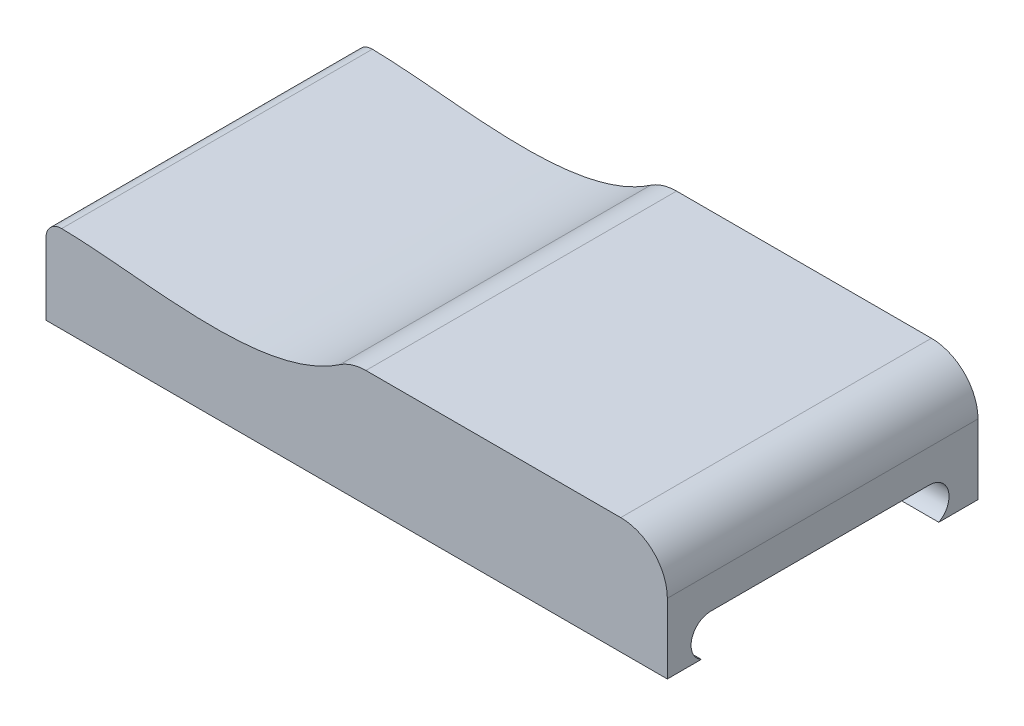
SolidWorks part; units mm, degrees
ref_plane "Front Plane" through (0, 0, 0) normal (0, 0, 1) x (1, 0, 0)
ref_plane "Top Plane" through (0, 0, 0) normal (0, 1, 0) x (1, 0, 0)
ref_plane "Right Plane" through (0, 0, 0) normal (1, 0, 0) x (0, 0, -1)
sketch "Sketch1" plane through (0, 0, 0) normal (0, 1, 0) x (1, 0, 0)
  line L1 (-200, -100) -> (200, -100)
  line L2 (-200, -100) -> (-200, 100)
  line L3 (-200, 100) -> (200, 100)
  line L4 (200, -100) -> (200, 100)
  line L5 (-200, -100) -> (200, 100) construction
  line L6 (-200, 100) -> (200, -100) construction
  point P0 (0, 0)
  dimension "D1" = 400
  dimension "D2" = 200
extrude "Boss-Extrude1" add sketch "Sketch1" along normal blind 60 contours L3 L4 L1 L2
sketch "Sketch3" plane through (0, 0, 100) normal (0, 0, 1) x (1, 0, 0)
  line L2 (-200, 60) -> (-200, 0) construction
  line L3 (-200, 60) -> (200, 60) construction
  line L4 (-200, 41.0333) -> (-200, 60)
  line L5 (-200, 60) -> (-3.947, 60)
  spline S0 degree 3 poles (-200, 41.0333) (-145.1623, 43.5654) (-56.827, 16.6615) (-3.947, 60) knots 0 0 0 0 1 1 1 1
extrude "Cut-Extrude1" cut sketch "Sketch3" against normal blind 220
fillet "Fillet1" radius 30 2 edges at (-3.947, 60, 0) (200, 60, 0)
fillet "Fillet2" radius 10 1 edges at (-200, 41.0333, 0)
sketch "Sketch9" plane through (0, 0, 0) normal (0, -1, 0) x (1, 0, 0)
  line L4 (-200, 100) -> (-200, -100)
  line L5 (-200, -100) -> (200, -100)
  line L6 (200, -100) -> (200, 100)
  line L7 (200, 100) -> (-200, 100)
  line L8 (-200, 100) -> (-200, -100)
  line L9 (-200, -100) -> (200, -100)
  line L10 (200, -100) -> (200, 100)
  line L11 (200, 100) -> (-200, 100)
  dimension "D1" = 0
extrude "Boss-Extrude4" add sketch "Sketch9" along normal blind 15
sketch "Sketch10" plane through (-200, 0, 0) normal (-1, 0, 0) x (0, 0, 1)
  line L2 (1.6743, -15) -> (1.6743, 14.9041) construction
  line L6 (-68.6457, 8.8299) -> (71.9943, 8.8299)
  line L7 (-74.7625, -15) -> (78.1112, -15)
  line L8 (100, -15) -> (-100, -15) construction
  line L9 (1.6743, -15) -> (-74.7625, -15)
  arc A4 (-68.6457, 8.8299) -> (-74.7625, -15) centre (-68.6457, -3.8701) ccw
  arc A5 (71.9943, 8.8299) -> (78.1112, -15) centre (71.9943, -3.8701) cw
  point P5 (4.7375, -15)
  point P12 (1.6743, 8.8299)
  point P14 (1.6743, -2.5834)
  line M11 (-100, -15) -> (100, -15)
  dimension "D2" = 25.4
  dimension "D1" = 70.32
extrude "Cut-Extrude9" cut sketch "Sketch10" against normal through all contours L2 L6 A4 M11 | L2 L7 A5 L6
